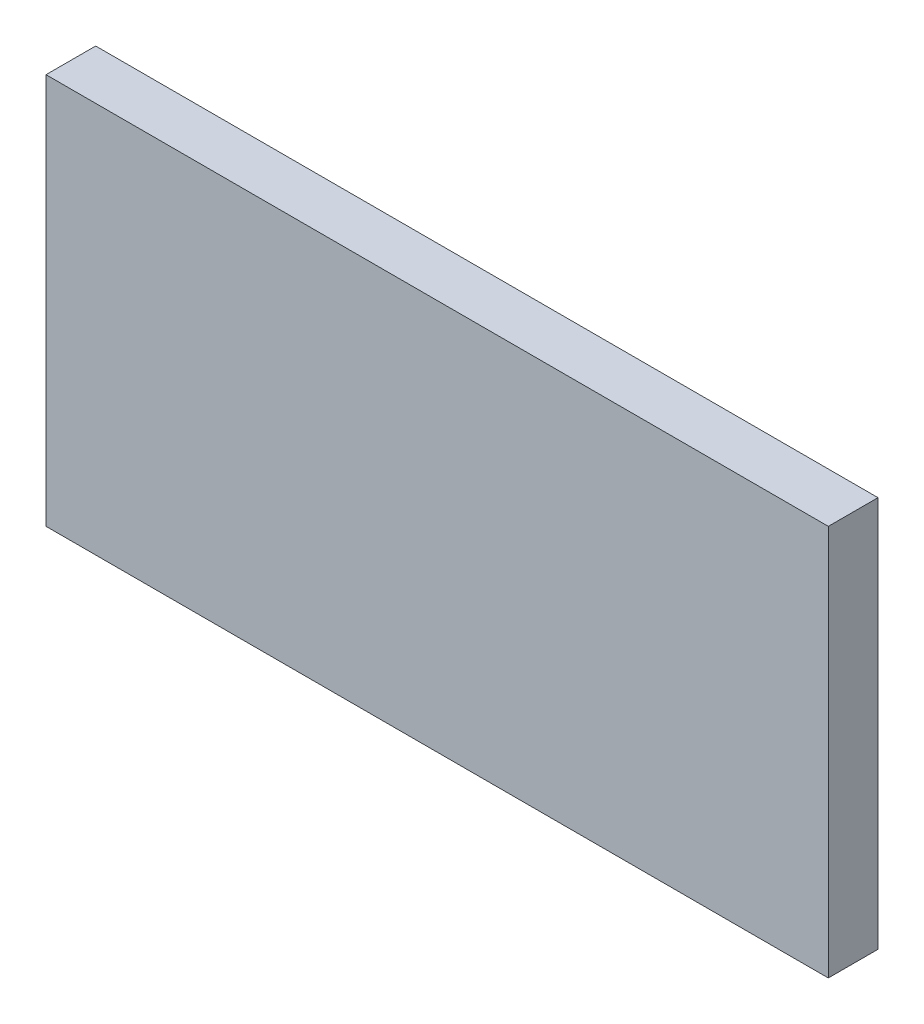
SolidWorks part; units mm, degrees
material "NEOPRENE"
ref_plane "Front Plane" through (0, 0, 0) normal (0, 0, 1) x (1, 0, 0)
ref_plane "Top Plane" through (0, 0, 0) normal (0, 1, 0) x (1, 0, 0)
ref_plane "Right Plane" through (0, 0, 0) normal (1, 0, 0) x (0, 0, -1)
sketch "Sketch1" plane through (0, 0, 0) normal (0, 0, 1) x (1, 0, 0)
  line L1 (0, 0) -> (50, 0)
  line L2 (0, 0) -> (0, 25)
  line L3 (0, 25) -> (50, 25)
  line L4 (50, 0) -> (50, 25)
  dimension "D1" = 50
  dimension "D2" = 25
extrude "base" add sketch "Sketch1" along normal blind 3.175
